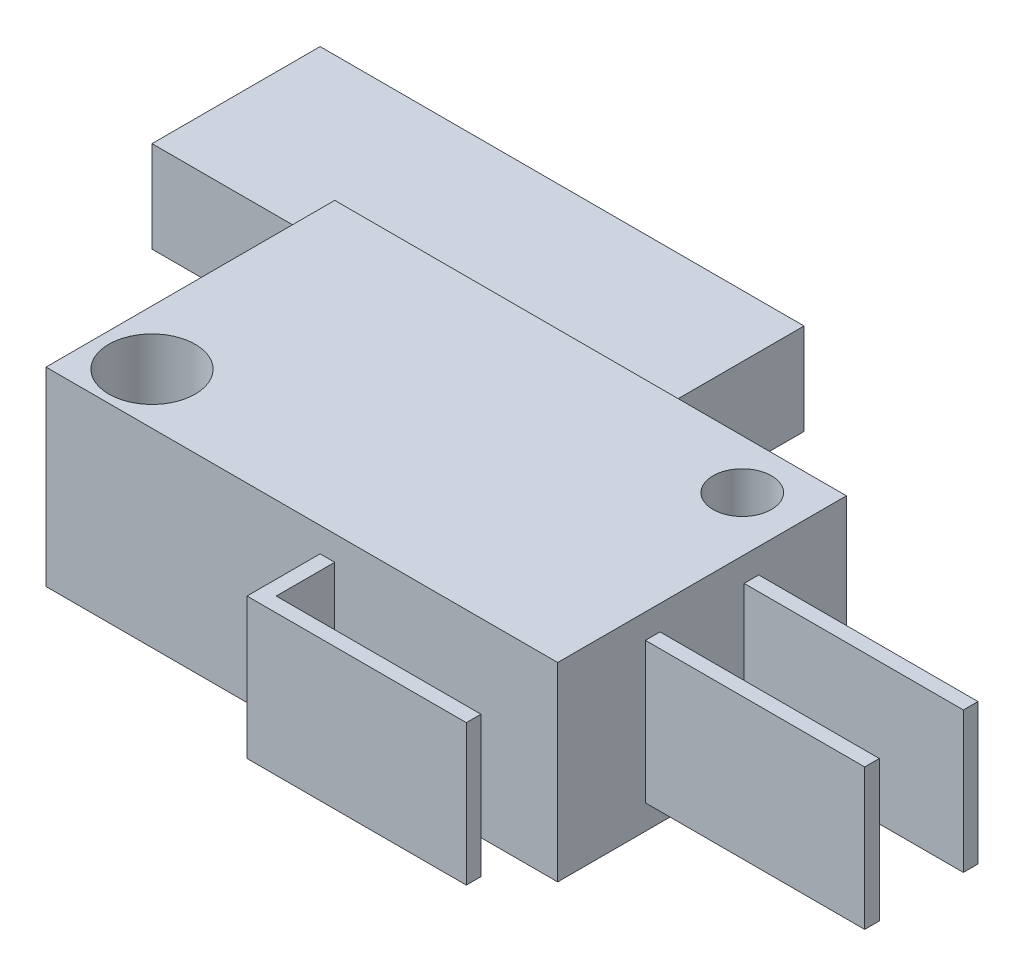
SolidWorks part; units mm, degrees
ref_plane "Front Plane" through (0, 0, 0) normal (0, 0, 1) x (1, 0, 0)
ref_plane "Top Plane" through (0, 0, 0) normal (0, 1, 0) x (1, 0, 0)
ref_plane "Right Plane" through (0, 0, 0) normal (1, 0, 0) x (0, 0, -1)
sketch "Sketch1" plane through (0, 0, 0) normal (0, 1, 0) x (1, 0, 0)
  line L1 (0, 0) -> (28, 0)
  line L2 (0, 0) -> (0, 15.8)
  line L3 (0, 15.8) -> (28, 15.8)
  line L4 (28, 0) -> (28, 15.8)
  dimension "D1" = 28
  dimension "D2" = 15.8
extrude "Base" add sketch "Sketch1" along normal blind 10.4
sketch "Sketch2" plane through (28, 0, 0) normal (1, 0, 0) x (0, 0, -1)
  line L0 (4.8, 1.35) -> (0, 1.35) construction
  line L1 (4.8, 9.05) -> (5.6, 9.05)
  line L2 (4.8, 9.05) -> (4.8, 1.35)
  line L3 (4.8, 1.35) -> (5.6, 1.35)
  line L4 (5.6, 9.05) -> (5.6, 1.35)
  line L5 (10.2, 9.05) -> (11, 9.05)
  line L6 (10.2, 9.05) -> (10.2, 1.35)
  line L7 (10.2, 1.35) -> (11, 1.35)
  line L8 (11, 9.05) -> (11, 1.35)
  line L9 (0, 10.4) -> (0, 0) construction
  line L10 (11, 1.35) -> (15.8, 1.35) construction
  line L11 (15.8, 10.4) -> (15.8, 0) construction
  line L12 (5.6, 1.35) -> (5.6, 0) construction
  line L13 (0, 0) -> (15.8, 0) construction
  line L14 (10.2, 1.35) -> (10.2, 0) construction
  line L15 (5.6, 9.05) -> (5.6, 10.4) construction
  line L16 (0, 10.4) -> (15.8, 10.4) construction
  line L17 (10.2, 9.05) -> (10.2, 10.4) construction
  dimension "D1" = 7.7
  dimension "D2" = 0.8
  dimension "D3" = 6.2
extrude "End Prongs" add sketch "Sketch2" along normal blind 12
sketch "Sketch3" plane through (0, 0, 0) normal (0, 0, 1) x (1, 0, 0)
  line L0 (15, 9.05) -> (15, 10.4) construction
  line L1 (15, 9.05) -> (27, 9.05)
  line L2 (15, 9.05) -> (15, 1.35)
  line L3 (15, 1.35) -> (27, 1.35)
  line L4 (27, 9.05) -> (27, 1.35)
  line L5 (0, 10.4) -> (28, 10.4) construction
  line L6 (15, 1.35) -> (15, 0) construction
  line L7 (0, 0) -> (28, 0) construction
  line L8 (0, 10.4) -> (0, 0) construction
  dimension "D1" = 15
  dimension "D2" = 12
  dimension "D3" = 7.7
extrude "Side Prong Extrude" add sketch "Sketch3" along normal blind 4
sketch "Sketch4" plane through (0, 9.05, 0) normal (0, 1, 0) x (1, 0, 0)
  line L0 (27, 0) -> (15, 0) construction
  line L1 (15.8, 0) -> (27, 0)
  line L2 (15.8, 0) -> (15.8, -3.2)
  line L3 (15.8, -3.2) -> (27, -3.2)
  line L4 (27, 0) -> (27, -3.2)
  line L5 (27, -4) -> (27, 0) construction
  line L6 (15, -4) -> (15, 0) construction
  line L7 (27, -4) -> (15, -4) construction
  dimension "D1" = 0.8
  dimension "D2" = 0.8
extrude "Side Prong Cut" cut sketch "Sketch4" against normal through all
sketch "Sketch6" plane through (0, 10.4, 0) normal (0, 1, 0) x (1, 0, 0)
  line L0 (28, 15.8) -> (0, 15.8) construction
  line L1 (3, 2.8) -> (0, 2.8) construction
  line L3 (0, 15.8) -> (0, 0) construction
  line L5 (25, 13.1) -> (28, 13.1) construction
  line L6 (28, 0) -> (28, 15.8) construction
  circle A0 centre (25, 13.1) radius 1.6
  circle A1 centre (3, 2.8) radius 2.365
  dimension "D1" = 3.2
  dimension "D2" = 2.7
  dimension "D3" = 22
  dimension "D4" = 10.3
  dimension "D5" = 4.73
extrude "Holes" cut sketch "Sketch6" against normal through all
sketch "Sketch5" plane through (0, 0, -15.8) normal (0, 0, -1) x (-1, 0, 0)
  line L0 (0, 10.4) -> (0, 0) construction
  line L1 (0, 8.0891) -> (-16.4819, 8.0891)
  line L2 (0, 8.0891) -> (0, 3.0891)
  line L3 (0, 3.0891) -> (-16.4819, 3.0891)
  line L4 (-16.4819, 8.0891) -> (-16.4819, 3.0891)
  line L5 (-16.4819, 8.0891) -> (-16.4819, 10.4) construction
  line L6 (-28, 10.4) -> (0, 10.4) construction
  line L7 (-16.4819, 3.0891) -> (-16.4819, 0) construction
  line L8 (-28, 0) -> (0, 0) construction
  dimension "D1" = 5
extrude "Boss-Extrude4" add sketch "Sketch5" along normal blind 9.2
sketch "Sketch7" plane through (0, 0, 0) normal (-1, 0, 0) x (0, 0, 1)
  line L1 (-25, 8.0891) -> (-15.8, 8.0891)
  line L2 (-25, 8.0891) -> (-25, 3.0891)
  line L3 (-25, 3.0891) -> (-15.8, 3.0891)
  line L4 (-15.8, 8.0891) -> (-15.8, 3.0891)
extrude "Boss-Extrude5" add sketch "Sketch7" along normal blind 10
